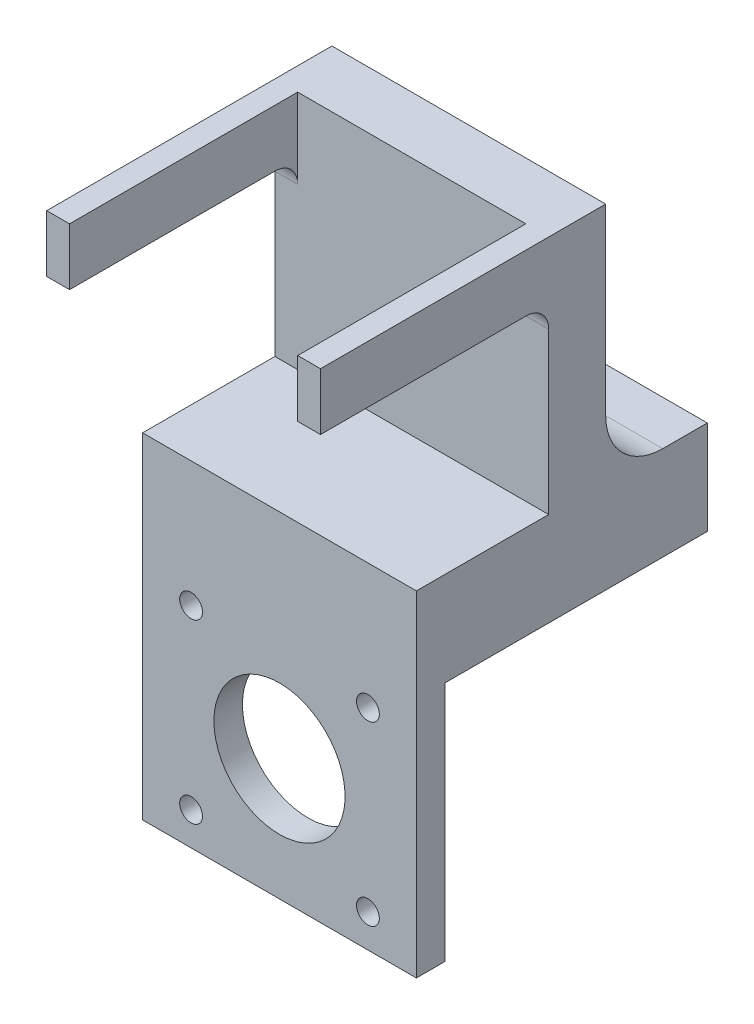
SolidWorks part; units mm, degrees
ref_plane "Front Plane" through (0, 0, 0) normal (0, 0, 1) x (1, 0, 0)
ref_plane "Top Plane" through (0, 0, 0) normal (0, 1, 0) x (1, 0, 0)
ref_plane "Right Plane" through (0, 0, 0) normal (1, 0, 0) x (0, 0, -1)
sketch "Sketch1" plane through (0, 0, 0) normal (0, 0, 1) x (1, 0, 0)
  line L1 (0, 0) -> (48, 0)
  line L2 (0, 0) -> (0, 53)
  line L3 (0, 53) -> (48, 53)
  line L4 (48, 0) -> (48, 53)
  dimension "D1" = 53
  dimension "D2" = 48
extrude "Boss-Extrude1" add sketch "Sketch1" along normal blind 10
sketch "Sketch2" plane through (0, 0, 0) normal (0, 0, -1) x (-1, 0, 0)
  line L0 (0, 53) -> (0, 0) construction
  line L1 (-48, 0) -> (0, 0)
  line L2 (-48, 0) -> (-48, -5.6163)
  line L3 (-48, -5.6163) -> (0, -5.6163)
  line L4 (0, 0) -> (0, -5.6163)
  dimension "D1" = 5.6163
extrude "Boss-Extrude2" add sketch "Sketch2" against normal blind 33.1918
sketch "Sketch4" plane through (0, 0, 10) normal (0, 0, 1) x (1, 0, 0)
  line L1 (0, 53) -> (4, 53)
  line L2 (0, 53) -> (0, 43)
  line L3 (0, 43) -> (4, 43)
  line L4 (4, 53) -> (4, 43)
  line L5 (48, 53) -> (44, 53)
  line L6 (48, 53) -> (48, 43)
  line L7 (48, 43) -> (44, 43)
  line L8 (44, 53) -> (44, 43)
  dimension "D1" = 10
  dimension "D2" = 4
extrude "Boss-Extrude4" add sketch "Sketch4" along normal blind 40
sketch "Sketch5" plane through (0, 0, 10) normal (0, 0, 1) x (1, 0, 0)
  line L0 (48, 0) -> (48, 43) construction
  line L1 (0, 0) -> (48, 0)
  line L2 (0, 0) -> (0, 10.8609)
  line L3 (0, 10.8609) -> (48, 10.8609)
  line L4 (48, 0) -> (48, 10.8609)
  dimension "D1" = 10.8609
extrude "Boss-Extrude5" add sketch "Sketch5" along normal up to surface (23.1918 mm away) up to face at (24, -2.8082, 33.1918)
sketch "Sketch6" plane through (0, -5.6163, 0) normal (0, -1, 0) x (1, 0, 0)
  line L0 (0, 0) -> (0, 28.1918) construction
  line L1 (0, 33.1918) -> (0, 0) construction
  line L2 (48, 33.1918) -> (48, 0) construction
  line L3 (0, 28.1918) -> (48, 28.1918)
  line L4 (0, 28.1918) -> (0, 33.1918)
  line L5 (0, 33.1918) -> (48, 33.1918)
  line L6 (48, 28.1918) -> (48, 33.1918)
  line L8 (48, 33.1918) -> (0, 33.1918) construction
  dimension "D2" = 5
extrude "Boss-Extrude6" add sketch "Sketch6" along normal blind 42.3
sketch "Sketch7" plane through (0, 0, 0) normal (-1, 0, 0) x (0, 0, 1)
  line L0 (33.1918, 10.8609) -> (10, 10.8609) construction
  line L1 (0, -5.6163) -> (-12.8082, -5.6163)
  line L2 (0, -5.6163) -> (0, 10.8609)
  line L3 (0, 10.8609) -> (-12.8082, 10.8609)
  line L4 (-12.8082, -5.6163) -> (-12.8082, 10.8609)
  line L5 (28.1918, -47.9163) -> (28.1918, -5.6163) construction
  dimension "D1" = 41
extrude "Boss-Extrude7" add sketch "Sketch7" against normal up to surface (48 mm away) up to face at (48, 10.6657, 24.2767)
sketch "Sketch8" plane through (0, 0, 28.1918) normal (0, 0, -1) x (-1, 0, 0)
  line L0 (-24, -26.6163) -> (-24, -5.6163) construction
  line L1 (0, -5.6163) -> (-48, -5.6163) construction
  line L3 (-8.5, -42.1163) -> (-39.5, -42.1163) construction
  line L4 (-8.5, -42.1163) -> (-8.5, -11.1163) construction
  line L5 (-8.5, -11.1163) -> (-39.5, -11.1163) construction
  line L6 (-39.5, -42.1163) -> (-39.5, -11.1163) construction
  line L7 (-8.5, -42.1163) -> (-39.5, -11.1163) construction
  line L8 (-8.5, -11.1163) -> (-39.5, -42.1163) construction
  circle A0 centre (-24, -26.6163) radius 11.5
  circle A1 centre (-39.5, -11.1163) radius 2
  circle A2 centre (-39.5, -42.1163) radius 2
  circle A3 centre (-8.5, -11.1163) radius 2
  circle A4 centre (-8.5, -42.1163) radius 2
  dimension "D2" = 23
  dimension "D4" = 4
  dimension "D1" = 21
  dimension "D3" = 31
extrude "Cut-Extrude1" cut sketch "Sketch8" against normal up to next
fillet "Fillet1" radius 10 1 edges at (24, 10.8609, 0)
fillet "Fillet2" radius 4 2 edges at (2, 43, 10) (46, 43, 10)
sketch "Sketch9" plane through (48, 0, 0) normal (1, 0, 0) x (0, 0, -1)
  line L1 (12.8082, 10.8609) -> (17.8082, 10.8609)
  line L2 (12.8082, 10.8609) -> (12.8082, -5.6163)
  line L3 (12.8082, -5.6163) -> (17.8082, -5.6163)
  line L4 (17.8082, 10.8609) -> (17.8082, -5.6163)
  line L5 (-28.1918, -5.6163) -> (12.8082, -5.6163) construction
  dimension "D1" = 5
extrude "Boss-Extrude9" add sketch "Sketch9" against normal up to surface (48 mm away) contours L4 L3 L2 L1 up to face at (0, 13.3569, 15.8852)
